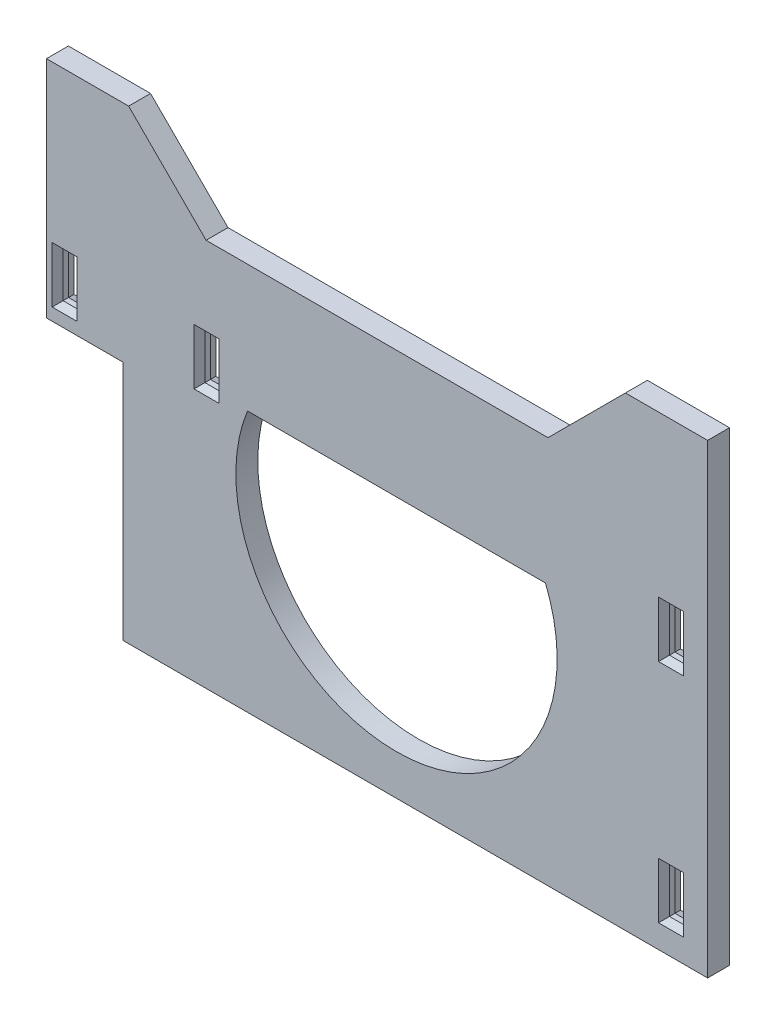
SolidWorks part; units mm, degrees
ref_plane "Front Plane" through (0, 0, 0) normal (0, 0, 1) x (1, 0, 0)
ref_plane "Top Plane" through (0, 0, 0) normal (0, 1, 0) x (1, 0, 0)
ref_plane "Right Plane" through (0, 0, 0) normal (1, 0, 0) x (0, 0, -1)
sketch "Sketch1" plane through (0, 0, 0) normal (0, 0, 1) x (1, 0, 0)
  line L0 (-31.5106, 17.6478) -> (22.8986, 17.6478)
  line L6 (-40.7725, 25.95) -> (-37.2425, 25.95)
  line L9 (-40.7725, 25.95) -> (-40.7725, 16.75)
  line L12 (-40.7725, 16.75) -> (-37.2425, 16.75)
  line L15 (-37.2425, 25.95) -> (-37.2425, 16.75)
  line L51 (52.4925, 30) -> (52.4925, -30)
  line L54 (44.0275, 25.25) -> (47.5575, 25.25)
  line L55 (44.0275, 25.25) -> (44.0275, 16.05)
  line L56 (44.0275, 16.05) -> (47.5575, 16.05)
  line L57 (47.5575, 25.25) -> (47.5575, 16.05)
  line L58 (47.565, -16.05) -> (44.035, -16.05)
  line L59 (47.565, -16.05) -> (47.565, -25.25)
  line L60 (47.565, -25.25) -> (44.035, -25.25)
  line L61 (44.035, -16.05) -> (44.035, -25.25)
  line L65 (-66.6725, 25.95) -> (-63.1425, 25.95)
  line L66 (-66.6725, 25.95) -> (-66.6725, 16.75)
  line L67 (-66.6725, 16.75) -> (-63.1425, 16.75)
  line L68 (-63.1425, 25.95) -> (-63.1425, 16.75)
  line L76 (52.4925, 30) -> (-68.2075, 30)
  line L81 (-39.0075, 25.95) -> (-39.0075, 16.75) construction
  line L82 (-37.2425, 21.35) -> (-40.7725, 21.35) construction
  line L83 (-64.9075, 25.95) -> (-64.9075, 16.75) construction
  line L84 (-63.1425, 21.35) -> (-66.6725, 21.35) construction
  line L85 (47.5575, 20.65) -> (44.0275, 20.65) construction
  line L86 (45.7925, 25.25) -> (45.7925, 16.05) construction
  line L87 (45.8, -16.05) -> (45.8, -25.25) construction
  line L88 (47.565, -20.65) -> (44.035, -20.65) construction
  line L89 (-54.2075, -30) -> (-54.2075, 14)
  line L90 (-54.2075, 14) -> (-68.2075, 14)
  line L91 (-68.2075, 14) -> (-68.2075, 30)
  line L92 (-54.2075, -30) -> (52.4925, -30)
  arc A12 (-31.5106, 17.6478) -> (22.8986, 17.6478) centre (-4.306, 6.6977) ccw
  point P0 (-0.0075, 0)
  point P14 (52.4925, 0)
  point P25 (-7.8575, 30)
  dimension "D3" = 3.53
  dimension "D4" = 9.2
  dimension "D6" = 60
  dimension "D5" = 25.9
  dimension "D7" = 53.65
  dimension "D2" = 31.15
  dimension "D10" = 20.65
  dimension "D11" = 20.65
  dimension "D8" = 120.7
  dimension "D9" = 14
  dimension "D12" = 44
extrude "Boss-Extrude1" add sketch "Sketch1" along normal blind 4
sketch "Sketch2" plane through (0, 0, 0) normal (0, 0, 1) x (1, 0, 0)
  line L0 (-68.2075, 30) -> (52.4925, 30)
  line L4 (23.3504, 40.8579) -> (-39.0654, 40.8579)
  line L5 (-39.0654, 40.8579) -> (-53.2075, 55)
  line L6 (-53.2075, 55) -> (-68.2075, 55)
  line L7 (-68.2075, 55) -> (-68.2075, 30)
  line L8 (23.3504, 40.8579) -> (37.4925, 55)
  line L9 (37.4925, 55) -> (52.4925, 55)
  line L10 (52.4925, 55) -> (52.4925, 30)
  line L12 (-68.2075, 30) -> (-68.2075, 14) construction
  dimension "D1" = 25
  dimension "D2" = 20
  dimension "D3" = 15
  dimension "D4" = 135
extrude "Boss-Extrude2" add sketch "Sketch2" along normal blind 4
sketch "Sketch3" plane through (0, 0, 0) normal (0, 0, -1) x (-1, 0, 0)
  line L0 (-45.7925, 25.25) -> (-45.7925, 16.05) construction
  line L1 (-47.5575, 25.25) -> (-44.0275, 25.25) construction
  line L2 (-44.0275, 16.05) -> (-47.5575, 16.05) construction
  line L3 (-47.5575, 20.65) -> (-44.0275, 20.65) construction
  line L4 (-47.5575, 16.05) -> (-47.5575, 25.25) construction
  line L5 (-44.0275, 25.25) -> (-44.0275, 16.05) construction
  line L6 (-45.8, -16.05) -> (-45.8, -25.25) construction
  line L7 (-47.565, -16.05) -> (-44.035, -16.05) construction
  line L8 (-44.035, -25.25) -> (-47.565, -25.25) construction
  line L9 (-47.565, -20.65) -> (-44.035, -20.65) construction
  line L10 (-47.565, -25.25) -> (-47.565, -16.05) construction
  line L11 (-44.035, -16.05) -> (-44.035, -25.25) construction
  line L12 (39.0075, 25.95) -> (39.0075, 16.75) construction
  line L13 (37.2425, 25.95) -> (40.7725, 25.95) construction
  line L14 (40.7725, 16.75) -> (37.2425, 16.75) construction
  line L15 (37.2425, 21.35) -> (40.7725, 21.35) construction
  line L16 (37.2425, 16.75) -> (37.2425, 25.95) construction
  line L17 (40.7725, 25.95) -> (40.7725, 16.75) construction
  line L18 (64.9075, 25.95) -> (64.9075, 16.75) construction
  line L19 (63.1425, 25.95) -> (66.6725, 25.95) construction
  line L20 (66.6725, 16.75) -> (63.1425, 16.75) construction
  line L21 (63.1425, 21.35) -> (66.6725, 21.35) construction
  line L22 (63.1425, 16.75) -> (63.1425, 25.95) construction
  line L23 (66.6725, 25.95) -> (66.6725, 16.75) construction
chamfer "Chamfer1" distance 1.5 distance2 0.5 16 edges at (45.8, -25.25, 0) (44.035, -20.65, 0) (45.8, -16.05, 0) (47.565, -20.65, 0) (-64.9075, 25.95, 0) (-63.1425, 21.35, 0) (-64.9075, 16.75, 0) (-66.6725, 21.35, 0) (-39.0075, 25.95, 0) (-37.2425, 21.35, 0) (-39.0075, 16.75, 0) (-40.7725, 21.35, 0) (45.7925, 25.25, 0) (47.5575, 20.65, 0) (45.7925, 16.05, 0) (44.0275, 20.65, 0)
chamfer "Chamfer2" distance 0.5 distance2 1.5 16 edges at (44.035, -20.65, 4) (45.8, -25.25, 4) (47.565, -20.65, 4) (45.8, -16.05, 4) (45.7925, 16.05, 4) (44.0275, 20.65, 4) (45.7925, 25.25, 4) (47.5575, 20.65, 4) (-64.9075, 16.75, 4) (-66.6725, 21.35, 4) (-64.9075, 25.95, 4) (-63.1425, 21.35, 4) (-40.7725, 21.35, 4) (-39.0075, 16.75, 4) (-39.0075, 25.95, 4) (-37.2425, 21.35, 4)
equation "\"pin_hole_width\"=3.53"
equation "\"D3@Sketch1\"=\"pin_hole_width\""
equation "\"pin_hole_height\"=9.2"
equation "\"D4@Sketch1\"=\"pin_hole_height\""
equation "\"distancer\"=24.9"
equation "\"D5@Sketch1\"=\"distancer\"+1"
